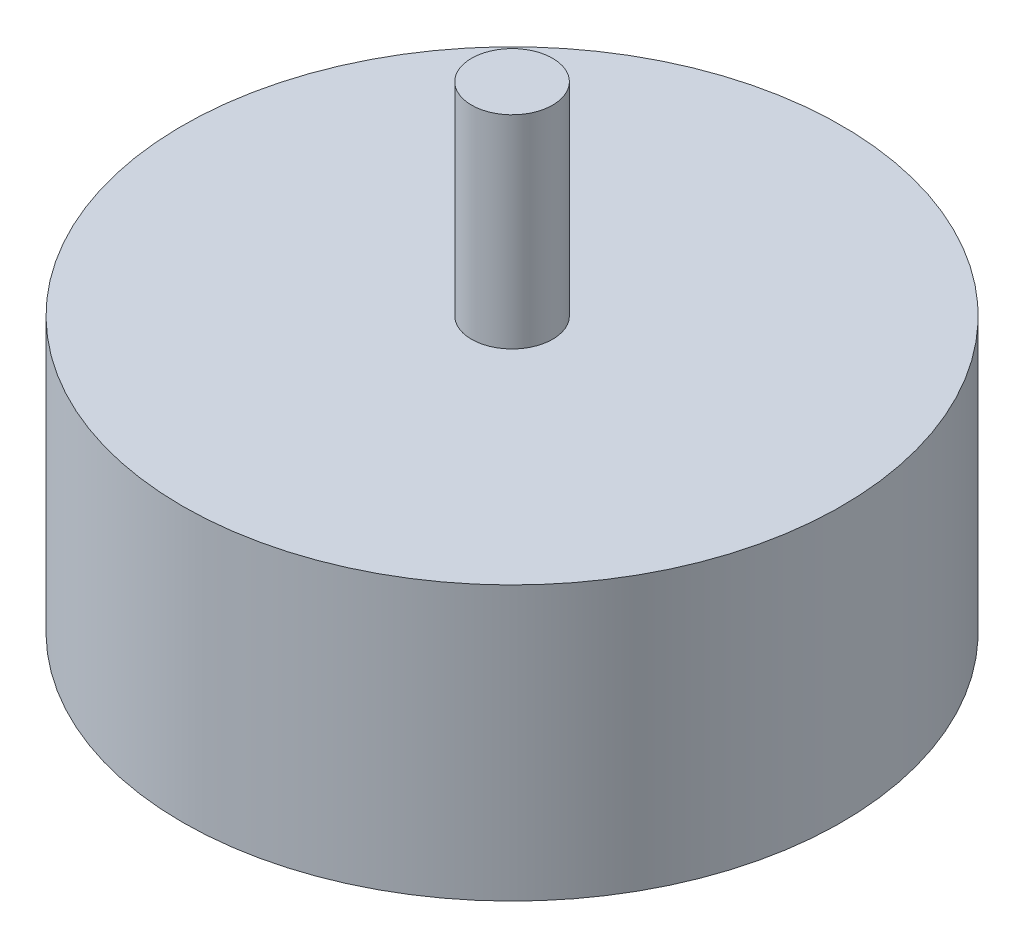
SolidWorks part; units mm, degrees
ref_plane "Front Plane" through (0, 0, 0) normal (0, 0, 1) x (1, 0, 0)
ref_plane "Top Plane" through (0, 0, 0) normal (0, 1, 0) x (1, 0, 0)
ref_plane "Right Plane" through (0, 0, 0) normal (1, 0, 0) x (0, 0, -1)
sketch "Sketch1" plane through (0, 0, 0) normal (0, 1, 0) x (1, 0, 0)
  circle A0 centre (0, 0) radius 32.5
  dimension "D1" = 65
extrude "Boss-Extrude1" add sketch "Sketch1" along normal blind 27
sketch "Sketch2" plane through (0, 27, 0) normal (0, 1, 0) x (1, 0, 0)
  circle A0 centre (0, 0) radius 4
  circle A1 centre (0, 0) radius 32.5 construction
  dimension "D1" = 8
extrude "Boss-Extrude2" add sketch "Sketch2" along normal blind 20
